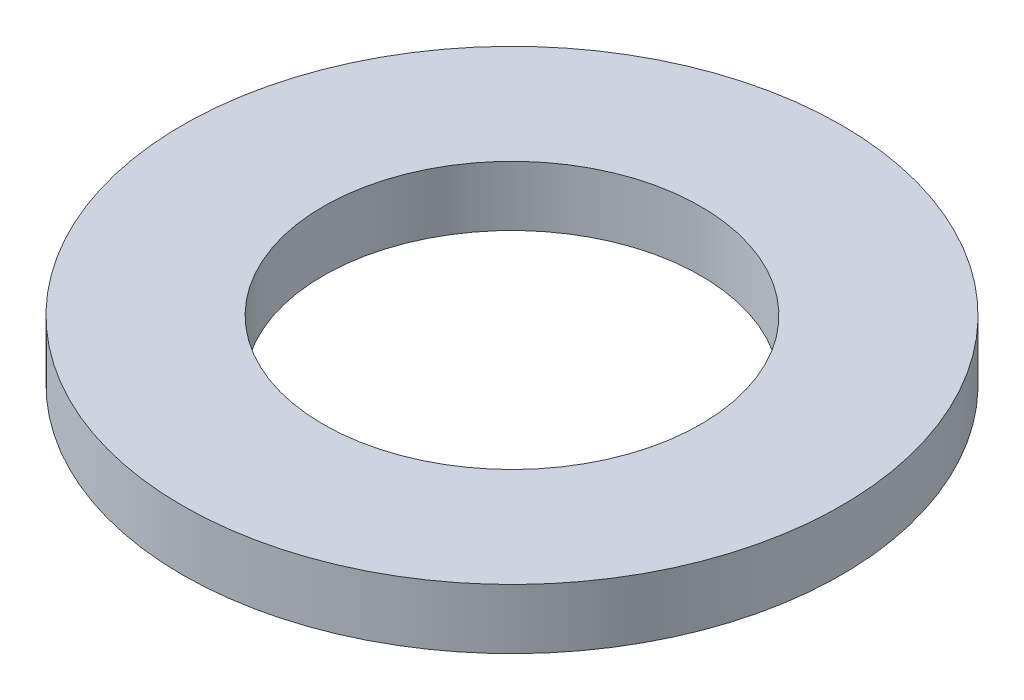
SolidWorks part; units mm, degrees
material "i190"
ref_plane "Front Plane" through (0, 0, 0) normal (0, 0, 1) x (1, 0, 0)
ref_plane "Top Plane" through (0, 0, 0) normal (0, 1, 0) x (1, 0, 0)
ref_plane "Right Plane" through (0, 0, 0) normal (1, 0, 0) x (0, 0, -1)
sketch "Sketch1" plane through (0, 0, 0) normal (0, 1, 0) x (1, 0, 0)
  circle A0 centre (0, 0) radius 5.5
  circle A1 centre (0, 0) radius 3.15
  dimension "D1" = 11
  dimension "D2" = 6.3
extrude "Boss-Extrude1" add sketch "Sketch1" along normal blind 1
